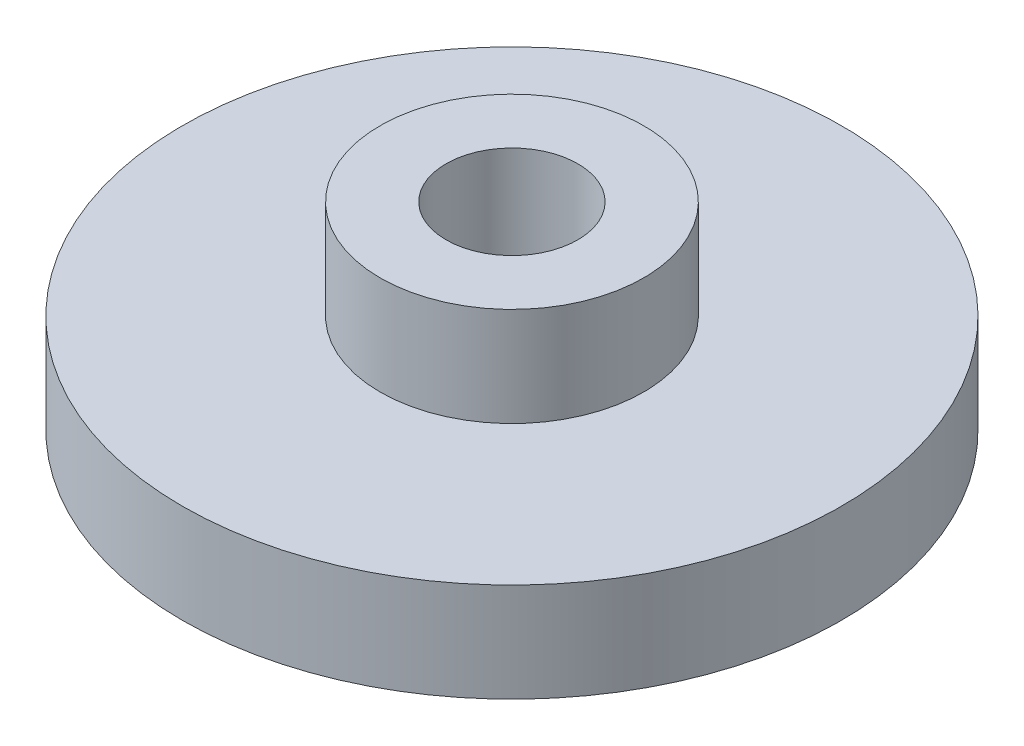
SolidWorks part; units mm, degrees
ref_plane "Front Plane" through (0, 0, 0) normal (0, 0, 1) x (1, 0, 0)
ref_plane "Top Plane" through (0, 0, 0) normal (0, 1, 0) x (1, 0, 0)
ref_plane "Right Plane" through (0, 0, 0) normal (1, 0, 0) x (0, 0, -1)
sketch "Sketch1" plane through (0, 0, 0) normal (0, 1, 0) x (1, 0, 0)
  circle A0 centre (0, 0) radius 20
  dimension "D1" = 40
extrude "Boss-Extrude1" add sketch "Sketch1" along normal blind 6
sketch "Sketch2" plane through (0, 6, 0) normal (0, 1, 0) x (1, 0, 0)
  circle A0 centre (0, 0) radius 8
  dimension "D1" = 16
extrude "Boss-Extrude2" add sketch "Sketch2" along normal blind 6
sketch "Sketch3" plane through (0, 12, 0) normal (0, 1, 0) x (1, 0, 0)
  circle A0 centre (0, 0) radius 4
  dimension "D1" = 8
extrude "Cut-Extrude1" cut sketch "Sketch3" against normal through all
